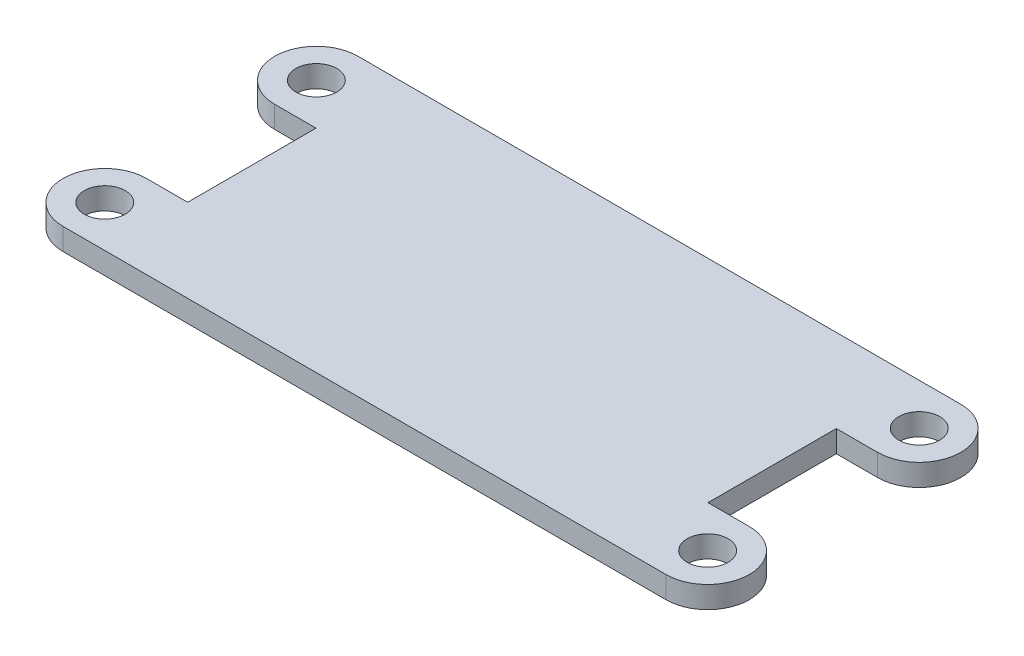
SolidWorks part; units mm, degrees
ref_plane "Front Plane" through (0, 0, 0) normal (0, 0, 1) x (1, 0, 0)
ref_plane "Top Plane" through (0, 0, 0) normal (0, 1, 0) x (1, 0, 0)
ref_plane "Right Plane" through (0, 0, 0) normal (1, 0, 0) x (0, 0, -1)
sketch "Sketch1" plane through (0, 0, 0) normal (0, 1, 0) x (1, 0, 0)
  line L0 (-19.05, -7.747) -> (-22.075, -7.747) construction
  line L1 (-19.05, -10.795) -> (19.05, -10.795)
  line L2 (-19.05, -10.795) -> (-19.05, 10.795)
  line L3 (-19.05, 10.795) -> (19.05, 10.795)
  line L4 (19.05, -10.795) -> (19.05, 10.795)
  line L5 (-19.05, -10.795) -> (19.05, 10.795) construction
  line L6 (-19.05, 10.795) -> (19.05, -10.795) construction
  line L7 (-19.05, -10.795) -> (-22.075, -10.795)
  line L8 (-19.05, -4.699) -> (-22.075, -4.699)
  line L9 (-55, 0) -> (55, 0) construction
  line L10 (-19.05, 7.747) -> (-22.075, 7.747) construction
  line L11 (-19.05, 10.795) -> (-22.075, 10.795)
  line L12 (-19.05, 4.699) -> (-22.075, 4.699)
  line L13 (0, -55) -> (0, 55) construction
  line L14 (19.05, 7.747) -> (22.075, 7.747) construction
  line L15 (19.05, 10.795) -> (22.075, 10.795)
  line L16 (19.05, 4.699) -> (22.075, 4.699)
  line L17 (19.05, -7.747) -> (22.075, -7.747) construction
  line L18 (19.05, -10.795) -> (22.075, -10.795)
  line L19 (19.05, -4.699) -> (22.075, -4.699)
  arc A0 (-19.05, -10.795) -> (-19.05, -4.699) centre (-19.05, -7.747) ccw
  arc A1 (-22.075, -4.699) -> (-22.075, -10.795) centre (-22.075, -7.747) ccw
  arc A2 (-19.05, 10.795) -> (-19.05, 4.699) centre (-19.05, 7.747) cw
  arc A3 (-22.075, 4.699) -> (-22.075, 10.795) centre (-22.075, 7.747) cw
  arc A4 (19.05, 10.795) -> (19.05, 4.699) centre (19.05, 7.747) ccw
  arc A5 (22.075, 4.699) -> (22.075, 10.795) centre (22.075, 7.747) ccw
  arc A6 (19.05, -10.795) -> (19.05, -4.699) centre (19.05, -7.747) cw
  arc A7 (22.075, -4.699) -> (22.075, -10.795) centre (22.075, -7.747) cw
  circle A8 centre (-22.075, -7.747) radius 1.5
  circle A9 centre (-22.075, 7.747) radius 1.5
  circle A10 centre (22.075, 7.747) radius 1.5
  circle A11 centre (22.075, -7.747) radius 1.5
  point P0 (0, 0)
  point P8 (-20.5625, -7.747)
  point P18 (-20.5625, 7.747)
  point P26 (20.5625, 7.747)
  point P32 (20.5625, -7.747)
  dimension "D5" = 3
  dimension "D1" = 21.59
  dimension "D2" = 38.1
  dimension "D3" = 6.096
  dimension "D4" = 44.15
extrude "Boss-Extrude1" add sketch "Sketch1" along normal mid plane 1.6 contours L1 A6 L4 A4 L3 A2 L2 A0 | L8 A1 L7 L2 A8 | L2 A0 | A2 L2 | A3 L12 L2 L11 A9 | L4 A4 | L16 A5 L15 L4 A10 | A7 L19 L4 L18 A11 | A6 L4
